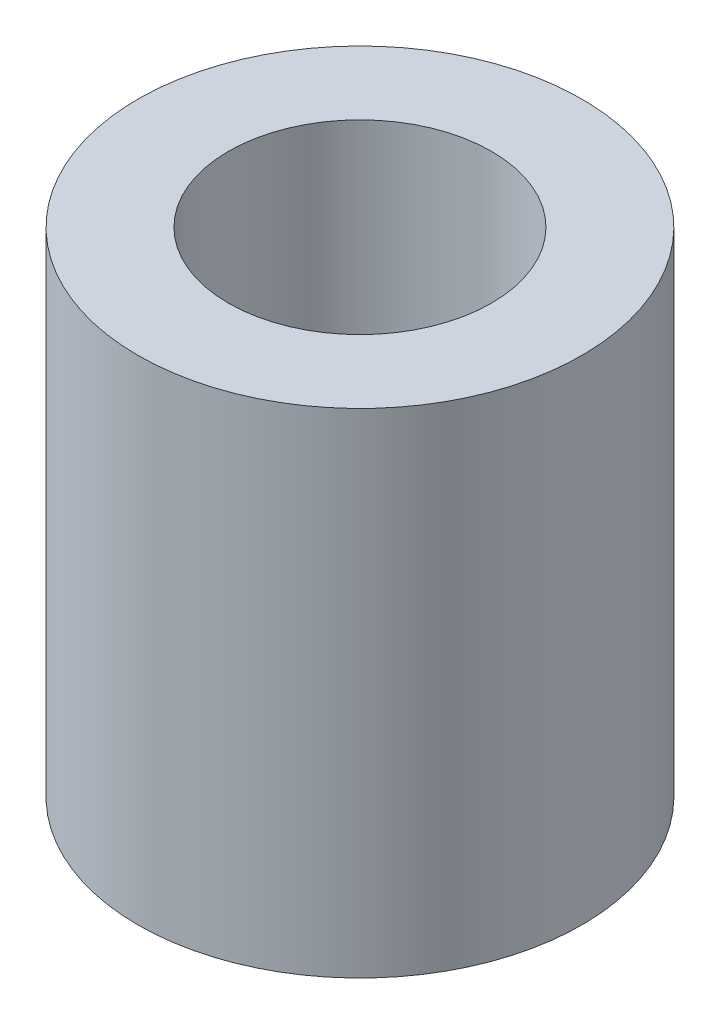
SolidWorks part; units mm, degrees
ref_plane "Front Plane" through (0, 0, 0) normal (0, 0, 1) x (1, 0, 0)
ref_plane "Top Plane" through (0, 0, 0) normal (0, 1, 0) x (1, 0, 0)
ref_plane "Right Plane" through (0, 0, 0) normal (1, 0, 0) x (0, 0, -1)
sketch "Sketch1" plane through (0, 0, 0) normal (0, 1, 0) x (1, 0, 0)
  circle A0 centre (0, 0) radius 3.375
  circle A1 centre (0, 0) radius 2
  dimension "D1" = 6.75
  dimension "D2" = 4
extrude "Boss-Extrude1" add sketch "Sketch1" along normal mid plane 7.5
